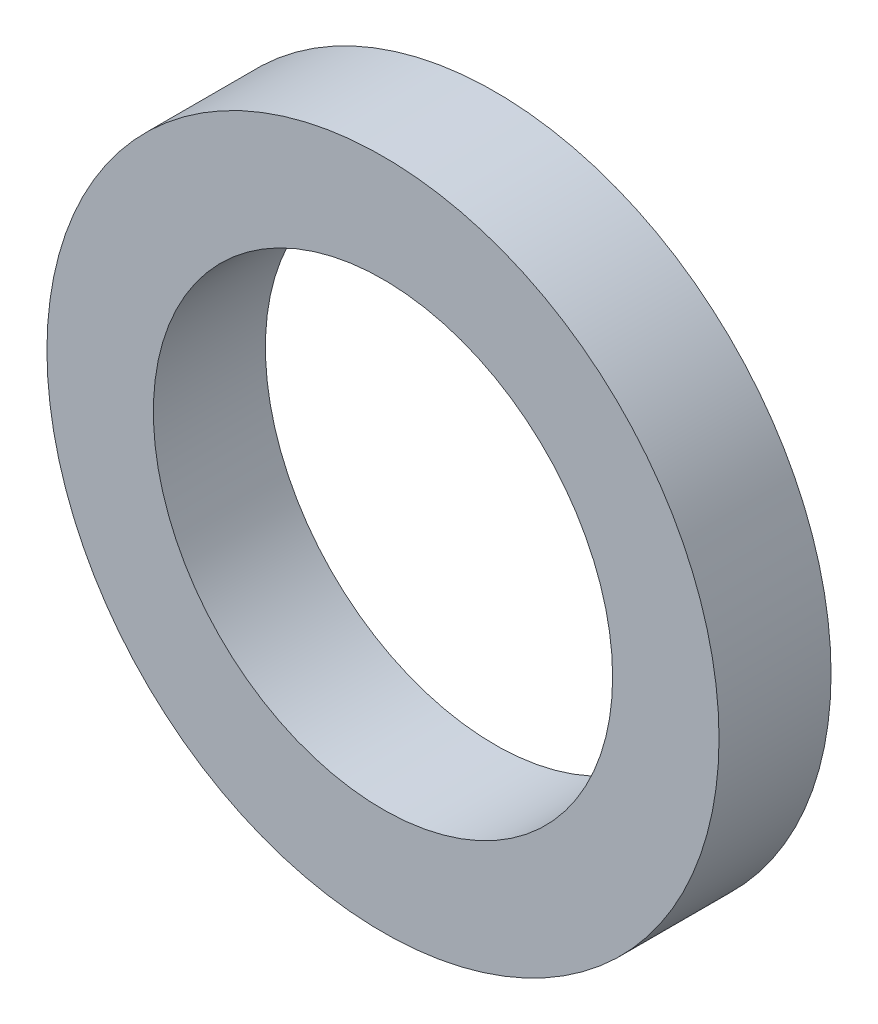
SolidWorks part; units mm, degrees
ref_plane "Front Plane" through (0, 0, 0) normal (1, 0, 0) x (0, 1, 0)
ref_plane "Top Plane" through (0, 0, 0) normal (0, 0, 1) x (0, 1, 0)
ref_plane "Right Plane" through (0, 0, 0) normal (0, 1, 0) x (-1, 0, 0)
sketch "Sketch1" plane through (0, 0, 0) normal (0, 0, 1) x (0, 1, 0)
  circle A0 centre (0, 0) radius 6
  circle A1 centre (0, 0) radius 4.1
  dimension "D1" = 12
  dimension "D2" = 8.2
extrude "Boss-Extrude1" add sketch "Sketch1" along normal blind 2
